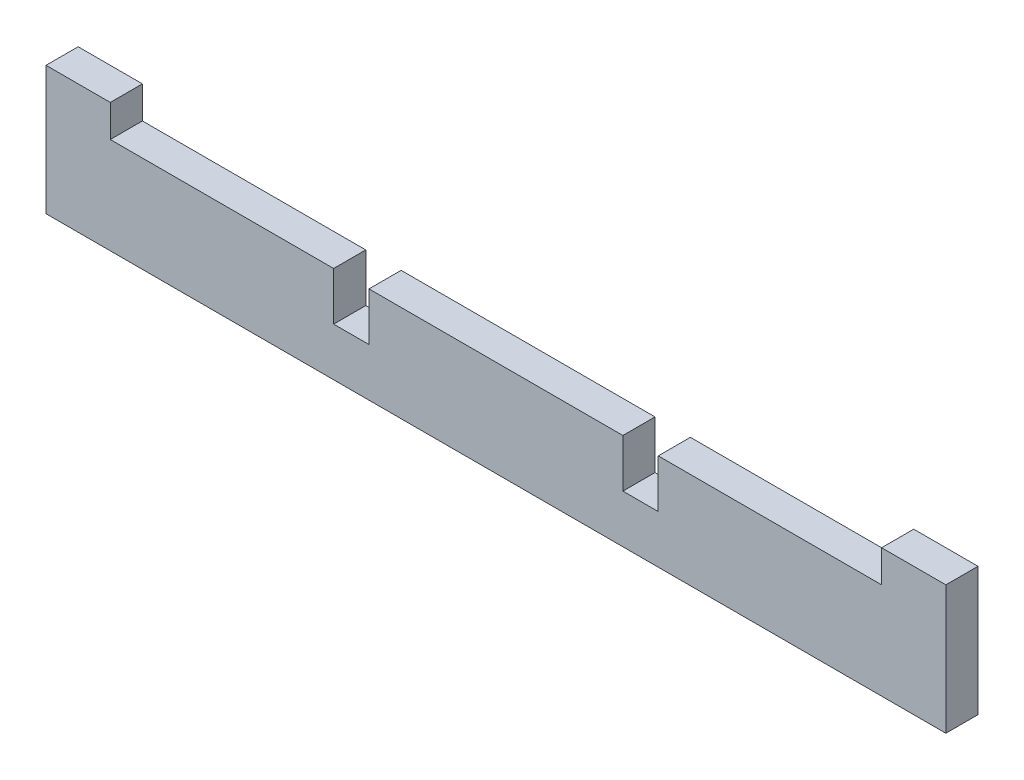
SolidWorks part; units mm, degrees
ref_plane "Front Plane" through (0, 0, 0) normal (0, 0, 1) x (1, 0, 0)
ref_plane "Top Plane" through (0, 0, 0) normal (0, 1, 0) x (1, 0, 0)
ref_plane "Right Plane" through (0, 0, 0) normal (1, 0, 0) x (0, 0, -1)
sketch "Model" plane through (0, 0, 0) normal (0, 0, 1) x (1, 0, 0)
  line L0 (628.5305, -196.1456) -> (628.5305, -188.6456)
  line L1 (663.2805, -183.6456) -> (673.2805, -183.6456)
  line L2 (543.2805, -183.6456) -> (543.2805, -188.6456)
  line L3 (673.2805, -183.6456) -> (673.2805, -203.6456)
  line L4 (578.0305, -188.6456) -> (578.0305, -196.1456)
  line L5 (533.2805, -203.6456) -> (533.2805, -183.6456)
  line L6 (663.2805, -188.6456) -> (663.2805, -183.6456)
  line L7 (533.2805, -183.6456) -> (543.2805, -183.6456)
  line L8 (543.2805, -188.6456) -> (578.0305, -188.6456)
  line L9 (583.5305, -188.6456) -> (623.0305, -188.6456)
  line L10 (663.2805, -188.6456) -> (628.5305, -188.6456)
  line L11 (623.0305, -188.6456) -> (623.0305, -196.1456)
  line L12 (583.5305, -196.1456) -> (583.5305, -188.6456)
  line L13 (578.0305, -196.1456) -> (583.5305, -196.1456)
  line L14 (623.0305, -196.1456) -> (628.5305, -196.1456)
  line L15 (673.2805, -203.6456) -> (533.2805, -203.6456)
  line L16 (607.4013, -190.2081) -> (607.4013, -192.4059)
  line L17 (607.4013, -192.4059) -> (606.3836, -192.4059)
  line L18 (606.3836, -192.4059) -> (605.8263, -192.3372)
  line L19 (605.8263, -192.3372) -> (605.4907, -192.2311)
  line L20 (605.4907, -192.2311) -> (605.3174, -192.0968)
  line L21 (605.3174, -192.0968) -> (605.2597, -191.9439)
  line L22 (605.2597, -191.9439) -> (605.2597, -190.6889)
  line L23 (605.2597, -190.6889) -> (605.2804, -190.5901)
  line L24 (605.2804, -190.5901) -> (605.3424, -190.5)
  line L25 (605.3424, -190.5) -> (605.5906, -190.3454)
  line L26 (605.5906, -190.3454) -> (605.9512, -190.2424)
  line L27 (605.9512, -190.2424) -> (606.3836, -190.2081)
  line L28 (606.3836, -190.2081) -> (607.4013, -190.2081)
  line L29 (607.4013, -194.516) -> (607.4013, -190.2081)
  line L30 (607.4013, -190.2081) -> (606.3836, -190.2081)
  line L31 (606.3836, -190.2081) -> (605.9512, -190.2424)
  line L32 (605.9512, -190.2424) -> (605.5906, -190.3454)
  line L33 (605.5906, -190.3454) -> (605.3424, -190.4999)
  line L34 (605.3424, -190.4999) -> (605.2804, -190.5901)
  line L35 (605.2804, -190.5901) -> (605.2597, -190.6888)
  line L36 (605.2597, -190.6888) -> (605.2597, -191.9437)
  line L37 (605.2597, -191.9437) -> (605.3174, -192.0967)
  line L38 (605.3174, -192.0967) -> (605.4907, -192.2309)
  line L39 (605.4907, -192.2309) -> (605.8263, -192.337)
  line L40 (605.8263, -192.337) -> (606.3836, -192.4057)
  line L41 (606.3836, -192.4057) -> (605.8326, -192.4697)
  line L42 (605.8326, -192.4697) -> (605.4907, -192.5743)
  line L43 (605.4907, -192.5743) -> (605.3174, -192.7132)
  line L44 (605.3174, -192.7132) -> (605.2597, -192.8677)
  line L45 (605.2597, -192.8677) -> (605.2597, -194.0352)
  line L46 (605.2597, -194.0352) -> (605.2804, -194.1289)
  line L47 (605.2804, -194.1289) -> (605.3424, -194.2163)
  line L48 (605.3424, -194.2163) -> (605.5906, -194.3724)
  line L49 (605.5906, -194.3724) -> (605.9543, -194.4801)
  line L50 (605.9543, -194.4801) -> (606.3836, -194.516)
  line L51 (606.3836, -194.516) -> (607.4013, -194.516)
  line L52 (606.3836, -192.4055) -> (607.4013, -192.4055)
  line L53 (607.4013, -192.4055) -> (607.4013, -194.516)
  line L54 (607.4013, -194.516) -> (606.3836, -194.516)
  line L55 (606.3836, -194.516) -> (605.9543, -194.4801)
  line L56 (605.9543, -194.4801) -> (605.5906, -194.3724)
  line L57 (605.5906, -194.3724) -> (605.3424, -194.2163)
  line L58 (605.3424, -194.2163) -> (605.2804, -194.1288)
  line L59 (605.2804, -194.1288) -> (605.2597, -194.0352)
  line L60 (605.2597, -194.0352) -> (605.2597, -192.8676)
  line L61 (605.2597, -192.8676) -> (605.3174, -192.713)
  line L62 (605.3174, -192.713) -> (605.4907, -192.5741)
  line L63 (605.4907, -192.5741) -> (605.8326, -192.4695)
  line L64 (605.8326, -192.4695) -> (606.3836, -192.4055)
  line L65 (604.4044, -190.2081) -> (604.4044, -194.516)
  line L66 (604.4044, -194.516) -> (602.2752, -194.516)
  line L67 (602.2752, -194.516) -> (604.4044, -194.516)
  line L68 (604.4044, -194.516) -> (604.4044, -192.4245)
  line L69 (604.4044, -192.4245) -> (602.5749, -192.4245)
  line L70 (602.5749, -192.4245) -> (604.4044, -192.4245)
  line L71 (604.4044, -192.4245) -> (604.4044, -190.2081)
  line L72 (604.4044, -190.2081) -> (602.2752, -190.2081)
  line L73 (602.2752, -190.2081) -> (604.4044, -190.2081)
  line L74 (600.2835, -190.2081) -> (600.7245, -190.2432)
  line L75 (600.7245, -190.2432) -> (601.0859, -190.3485)
  line L76 (601.0859, -190.3485) -> (601.3271, -190.5038)
  line L77 (601.3271, -190.5038) -> (601.3873, -190.5926)
  line L78 (601.3873, -190.5926) -> (601.4074, -190.6888)
  line L79 (601.4074, -190.6888) -> (601.3873, -190.5926)
  line L80 (601.3873, -190.5926) -> (601.3271, -190.5038)
  line L81 (601.3271, -190.5038) -> (601.0859, -190.3485)
  line L82 (601.0859, -190.3485) -> (600.7245, -190.2432)
  line L83 (599.8425, -190.2432) -> (599.4812, -190.3485)
  line L84 (599.4812, -190.3485) -> (599.24, -190.5038)
  line L85 (599.24, -190.5038) -> (599.1797, -190.5926)
  line L86 (599.1797, -190.5926) -> (599.1596, -190.6888)
  line L87 (599.1596, -190.6888) -> (599.1596, -192.3995)
  line L88 (599.1596, -192.3995) -> (599.1797, -192.4957)
  line L89 (599.1797, -192.4957) -> (599.24, -192.5845)
  line L90 (599.24, -192.5845) -> (599.4812, -192.7398)
  line L91 (599.4812, -192.7398) -> (599.8425, -192.8451)
  line L92 (599.8425, -192.8451) -> (600.2835, -192.8803)
  line L93 (600.2835, -192.8803) -> (600.9579, -192.7803)
  line L94 (600.9579, -192.7803) -> (601.1889, -192.6539)
  line L95 (601.1889, -192.6539) -> (601.4074, -192.3995)
  line L96 (601.4074, -192.3995) -> (601.4074, -194.516)
  line L97 (601.4074, -194.516) -> (599.2346, -194.516)
  line L98 (599.2346, -194.516) -> (601.4074, -194.516)
  line L99 (601.4074, -194.516) -> (601.4074, -192.3995)
  line L100 (601.4074, -192.3995) -> (601.1889, -192.6539)
  line L101 (601.1889, -192.6539) -> (600.9579, -192.7803)
  line L102 (600.9579, -192.7803) -> (600.2835, -192.8803)
  line L103 (600.2835, -192.8803) -> (599.8425, -192.8451)
  line L104 (599.8425, -192.8451) -> (599.4812, -192.7398)
  line L105 (599.4812, -192.7398) -> (599.24, -192.5845)
  line L106 (599.24, -192.5845) -> (599.1797, -192.4957)
  line L107 (599.1797, -192.4957) -> (599.1596, -192.3995)
  line L108 (599.1596, -192.3995) -> (599.1596, -190.6888)
  line L109 (599.1596, -190.6888) -> (599.1797, -190.5926)
  line L110 (599.1797, -190.5926) -> (599.24, -190.5038)
  line L111 (599.24, -190.5038) -> (599.4812, -190.3485)
  line L112 (599.4812, -190.3485) -> (599.8425, -190.2432)
  line L113 (599.8425, -190.2432) -> (600.2835, -190.2081)
  line L114 (609.9013, -192.3956) -> (614.9013, -192.3956)
  line L115 (612.9013, -193.3956) -> (614.9013, -192.3956)
  line L116 (612.9013, -191.3956) -> (614.9013, -192.3956)
  line L117 (596.6596, -192.3956) -> (591.6596, -192.3956)
  line L118 (593.6596, -191.3956) -> (591.6596, -192.3956)
  line L119 (593.6596, -193.3956) -> (591.6596, -192.3956)
  line L120 (538.2805, -190.6456) -> (538.2805, -185.6456)
  line L121 (539.2805, -187.6456) -> (538.2805, -185.6456)
  line L122 (537.2805, -187.6456) -> (538.2805, -185.6456)
  line L123 (542.4013, -191.6456) -> (542.4013, -193.8434)
  line L124 (542.4013, -193.8434) -> (541.3836, -193.8434)
  line L125 (541.3836, -193.8434) -> (540.8263, -193.7747)
  line L126 (540.8263, -193.7747) -> (540.4907, -193.6686)
  line L127 (540.4907, -193.6686) -> (540.3174, -193.5343)
  line L128 (540.3174, -193.5343) -> (540.2597, -193.3814)
  line L129 (540.2597, -193.3814) -> (540.2597, -192.1264)
  line L130 (540.2597, -192.1264) -> (540.2804, -192.0276)
  line L131 (540.2804, -192.0276) -> (540.3424, -191.9375)
  line L132 (540.3424, -191.9375) -> (540.5906, -191.7829)
  line L133 (540.5906, -191.7829) -> (540.9512, -191.6799)
  line L134 (540.9512, -191.6799) -> (541.3836, -191.6456)
  line L135 (541.3836, -191.6456) -> (542.4013, -191.6456)
  line L136 (542.4013, -195.9535) -> (542.4013, -191.6456)
  line L137 (542.4013, -191.6456) -> (541.3836, -191.6456)
  line L138 (541.3836, -191.6456) -> (540.9512, -191.6799)
  line L139 (540.9512, -191.6799) -> (540.5906, -191.7829)
  line L140 (540.5906, -191.7829) -> (540.3424, -191.9374)
  line L141 (540.3424, -191.9374) -> (540.2804, -192.0276)
  line L142 (540.2804, -192.0276) -> (540.2597, -192.1263)
  line L143 (540.2597, -192.1263) -> (540.2597, -193.3812)
  line L144 (540.2597, -193.3812) -> (540.3174, -193.5342)
  line L145 (540.3174, -193.5342) -> (540.4907, -193.6684)
  line L146 (540.4907, -193.6684) -> (540.8263, -193.7745)
  line L147 (540.8263, -193.7745) -> (541.3836, -193.8432)
  line L148 (541.3836, -193.8432) -> (540.8326, -193.9072)
  line L149 (540.8326, -193.9072) -> (540.4907, -194.0118)
  line L150 (540.4907, -194.0118) -> (540.3174, -194.1507)
  line L151 (540.3174, -194.1507) -> (540.2597, -194.3052)
  line L152 (540.2597, -194.3052) -> (540.2597, -195.4727)
  line L153 (540.2597, -195.4727) -> (540.2804, -195.5664)
  line L154 (540.2804, -195.5664) -> (540.3424, -195.6538)
  line L155 (540.3424, -195.6538) -> (540.5906, -195.8099)
  line L156 (540.5906, -195.8099) -> (540.9543, -195.9176)
  line L157 (540.9543, -195.9176) -> (541.3836, -195.9535)
  line L158 (541.3836, -195.9535) -> (542.4013, -195.9535)
  line L159 (541.3836, -193.843) -> (542.4013, -193.843)
  line L160 (542.4013, -193.843) -> (542.4013, -195.9535)
  line L161 (542.4013, -195.9535) -> (541.3836, -195.9535)
  line L162 (541.3836, -195.9535) -> (540.9543, -195.9176)
  line L163 (540.9543, -195.9176) -> (540.5906, -195.8099)
  line L164 (540.5906, -195.8099) -> (540.3424, -195.6538)
  line L165 (540.3424, -195.6538) -> (540.2804, -195.5663)
  line L166 (540.2804, -195.5663) -> (540.2597, -195.4727)
  line L167 (540.2597, -195.4727) -> (540.2597, -194.3051)
  line L168 (540.2597, -194.3051) -> (540.3174, -194.1505)
  line L169 (540.3174, -194.1505) -> (540.4907, -194.0116)
  line L170 (540.4907, -194.0116) -> (540.8326, -193.907)
  line L171 (540.8326, -193.907) -> (541.3836, -193.843)
  line L172 (539.4044, -191.6456) -> (539.4044, -195.9535)
  line L173 (539.4044, -195.9535) -> (538.3866, -195.9535)
  line L174 (538.3866, -195.9535) -> (537.9527, -195.9176)
  line L175 (537.9527, -195.9176) -> (537.5874, -195.8099)
  line L176 (537.5874, -195.8099) -> (537.3439, -195.6538)
  line L177 (537.3439, -195.6538) -> (537.283, -195.5664)
  line L178 (537.283, -195.5664) -> (537.2627, -195.4727)
  line L179 (537.2627, -195.4727) -> (537.2627, -192.1263)
  line L180 (537.2627, -192.1263) -> (537.283, -192.0299)
  line L181 (537.283, -192.0299) -> (537.3439, -191.9406)
  line L182 (537.3439, -191.9406) -> (537.5874, -191.7829)
  line L183 (537.5874, -191.7829) -> (537.9433, -191.6799)
  line L184 (537.9433, -191.6799) -> (538.3866, -191.6456)
  line L185 (538.3866, -191.6456) -> (539.4044, -191.6456)
  line L186 (539.4044, -195.9535) -> (539.4044, -191.6456)
  line L187 (539.4044, -191.6456) -> (538.3866, -191.6456)
  line L188 (538.3866, -191.6456) -> (537.9433, -191.6799)
  line L189 (537.9433, -191.6799) -> (537.5874, -191.7829)
  line L190 (537.5874, -191.7829) -> (537.3439, -191.9406)
  line L191 (537.3439, -191.9406) -> (537.283, -192.0299)
  line L192 (537.283, -192.0299) -> (537.2627, -192.1263)
  line L193 (537.2627, -192.1263) -> (537.2627, -195.4727)
  line L194 (537.2627, -195.4727) -> (537.283, -195.5664)
  line L195 (537.283, -195.5664) -> (537.3439, -195.6538)
  line L196 (537.3439, -195.6538) -> (537.5874, -195.8099)
  line L197 (537.5874, -195.8099) -> (537.9527, -195.9176)
  line L198 (537.9527, -195.9176) -> (538.3866, -195.9535)
  line L199 (538.3866, -195.9535) -> (539.4044, -195.9535)
  line L200 (535.2835, -191.6456) -> (535.7245, -191.6807)
  line L201 (535.7245, -191.6807) -> (536.0859, -191.786)
  line L202 (536.0859, -191.786) -> (536.3271, -191.9413)
  line L203 (536.3271, -191.9413) -> (536.3873, -192.0301)
  line L204 (536.3873, -192.0301) -> (536.4074, -192.1263)
  line L205 (536.4074, -192.1263) -> (536.3873, -192.0301)
  line L206 (536.3873, -192.0301) -> (536.3271, -191.9413)
  line L207 (536.3271, -191.9413) -> (536.0859, -191.786)
  line L208 (536.0859, -191.786) -> (535.7245, -191.6807)
  line L209 (534.8425, -191.6807) -> (534.4812, -191.786)
  line L210 (534.4812, -191.786) -> (534.24, -191.9413)
  line L211 (534.24, -191.9413) -> (534.1797, -192.0301)
  line L212 (534.1797, -192.0301) -> (534.1596, -192.1263)
  line L213 (534.1596, -192.1263) -> (534.1596, -193.837)
  line L214 (534.1596, -193.837) -> (534.1797, -193.9332)
  line L215 (534.1797, -193.9332) -> (534.24, -194.022)
  line L216 (534.24, -194.022) -> (534.4812, -194.1773)
  line L217 (534.4812, -194.1773) -> (534.8425, -194.2826)
  line L218 (534.8425, -194.2826) -> (535.2835, -194.3178)
  line L219 (535.2835, -194.3178) -> (535.9579, -194.2178)
  line L220 (535.9579, -194.2178) -> (536.1889, -194.0914)
  line L221 (536.1889, -194.0914) -> (536.4074, -193.837)
  line L222 (536.4074, -193.837) -> (536.4074, -195.9535)
  line L223 (536.4074, -195.9535) -> (534.2346, -195.9535)
  line L224 (534.2346, -195.9535) -> (536.4074, -195.9535)
  line L225 (536.4074, -195.9535) -> (536.4074, -193.837)
  line L226 (536.4074, -193.837) -> (536.1889, -194.0914)
  line L227 (536.1889, -194.0914) -> (535.9579, -194.2178)
  line L228 (535.9579, -194.2178) -> (535.2835, -194.3178)
  line L229 (535.2835, -194.3178) -> (534.8425, -194.2826)
  line L230 (534.8425, -194.2826) -> (534.4812, -194.1773)
  line L231 (534.4812, -194.1773) -> (534.24, -194.022)
  line L232 (534.24, -194.022) -> (534.1797, -193.9332)
  line L233 (534.1797, -193.9332) -> (534.1596, -193.837)
  line L234 (534.1596, -193.837) -> (534.1596, -192.1263)
  line L235 (534.1596, -192.1263) -> (534.1797, -192.0301)
  line L236 (534.1797, -192.0301) -> (534.24, -191.9413)
  line L237 (534.24, -191.9413) -> (534.4812, -191.786)
  line L238 (534.4812, -191.786) -> (534.8425, -191.6807)
  line L239 (534.8425, -191.6807) -> (535.2835, -191.6456)
  line L240 (640.7186, -192.7158) -> (641.4414, -192.9265)
  line L241 (650.9222, -196.9039) -> (652.0367, -197.0412)
  line L242 (648.0784, -192.6456) -> (648.0784, -197.0034)
  line L243 (649.9044, -197.6558) -> (650.251, -197.3776)
  line L244 (650.251, -196.6916) -> (650.9222, -196.9039)
  line L245 (649.8303, -193.4097) -> (649.7889, -193.6072)
  line L246 (649.8303, -193.4097) -> (649.9544, -193.2293)
  line L247 (650.9347, -197.1685) -> (650.251, -197.3776)
  line L248 (652.0367, -201.2614) -> (654.0723, -201.2614)
  line L249 (652.0367, -197.0412) -> (654.0723, -197.0412)
  line L250 (650.4508, -200.9743) -> (649.9544, -200.662)
  line L251 (649.9544, -200.662) -> (649.8303, -200.4872)
  line L252 (649.7889, -197.9646) -> (649.7889, -200.2998)
  line L253 (654.0723, -201.2614) -> (654.0723, -197.0412)
  line L254 (649.9544, -193.2293) -> (650.4508, -192.9203)
  line L255 (648.0784, -197.0034) -> (644.4194, -197.0034)
  line L256 (652.0367, -192.6456) -> (651.172, -192.7143)
  line L257 (651.1782, -201.1896) -> (650.4508, -200.9743)
  line L258 (651.172, -192.7143) -> (650.4508, -192.9203)
  line L259 (654.0723, -192.6456) -> (652.0367, -192.6456)
  line L260 (652.0367, -197.0412) -> (650.9347, -197.1685)
  line L261 (652.0367, -201.2614) -> (651.1782, -201.1896)
  line L262 (648.0784, -201.2614) -> (643.82, -201.2614)
  line L263 (654.0723, -197.0412) -> (654.0723, -192.6456)
  line L264 (649.7889, -200.2998) -> (649.8303, -200.4872)
  line L265 (639.8366, -192.6456) -> (640.7186, -192.7158)
  line L266 (641.9237, -193.2371) -> (642.0443, -193.4147)
  line L267 (642.0443, -193.4147) -> (642.0845, -193.6071)
  line L268 (650.251, -196.6916) -> (649.9044, -196.4231)
  line L269 (649.7889, -193.6072) -> (649.7889, -196.1172)
  line L270 (641.9237, -193.2371) -> (641.4414, -192.9265)
  line L271 (649.9044, -197.6558) -> (649.7889, -197.9646)
  line L272 (649.7889, -196.1172) -> (649.9044, -196.4231)
  line L273 (637.5888, -193.6071) -> (637.629, -193.4147)
  line L274 (642.0845, -197.0284) -> (641.6474, -197.5373)
  line L275 (638.9547, -197.9197) -> (639.8366, -197.99)
  line L276 (641.1854, -197.7901) -> (639.8366, -197.99)
  line L277 (638.9547, -197.9197) -> (638.2319, -197.709)
  line L278 (641.6474, -197.5373) -> (641.1854, -197.7901)
  line L279 (637.7496, -193.2371) -> (638.2319, -192.9265)
  line L280 (642.0845, -201.2614) -> (637.7387, -201.2614)
  line L281 (637.629, -193.4147) -> (637.7496, -193.2371)
  line L282 (648.0784, -197.0034) -> (648.0784, -201.2614)
  line L283 (637.7496, -197.3984) -> (637.629, -197.2208)
  line L284 (638.2319, -192.9265) -> (638.9547, -192.7158)
  line L285 (637.5888, -193.6071) -> (637.5888, -197.0284)
  line L286 (637.5888, -197.0284) -> (637.629, -197.2208)
  line L287 (637.7496, -197.3984) -> (638.2319, -197.709)
  line L288 (642.0845, -201.2614) -> (642.0845, -197.0284)
  line L289 (638.9547, -192.7158) -> (639.8366, -192.6456)
  line L290 (654.0723, -191.6456) -> (637.7387, -191.6456)
  line L291 (668.2805, -190.6456) -> (668.2805, -185.6456)
  line L292 (669.2805, -187.6456) -> (668.2805, -185.6456)
  line L293 (667.2805, -187.6456) -> (668.2805, -185.6456)
  line L294 (672.4013, -191.6456) -> (672.4013, -193.8434)
  line L295 (672.4013, -193.8434) -> (671.3836, -193.8434)
  line L296 (671.3836, -193.8434) -> (670.8263, -193.7747)
  line L297 (670.8263, -193.7747) -> (670.4907, -193.6686)
  line L298 (670.4907, -193.6686) -> (670.3174, -193.5343)
  line L299 (670.3174, -193.5343) -> (670.2597, -193.3814)
  line L300 (670.2597, -193.3814) -> (670.2597, -192.1264)
  line L301 (670.2597, -192.1264) -> (670.2804, -192.0276)
  line L302 (670.2804, -192.0276) -> (670.3424, -191.9375)
  line L303 (670.3424, -191.9375) -> (670.5906, -191.7829)
  line L304 (670.5906, -191.7829) -> (670.9512, -191.6799)
  line L305 (670.9512, -191.6799) -> (671.3836, -191.6456)
  line L306 (671.3836, -191.6456) -> (672.4013, -191.6456)
  line L307 (672.4013, -195.9535) -> (672.4013, -191.6456)
  line L308 (672.4013, -191.6456) -> (671.3836, -191.6456)
  line L309 (671.3836, -191.6456) -> (670.9512, -191.6799)
  line L310 (670.9512, -191.6799) -> (670.5906, -191.7829)
  line L311 (670.5906, -191.7829) -> (670.3424, -191.9374)
  line L312 (670.3424, -191.9374) -> (670.2804, -192.0276)
  line L313 (670.2804, -192.0276) -> (670.2597, -192.1263)
  line L314 (670.2597, -192.1263) -> (670.2597, -193.3812)
  line L315 (670.2597, -193.3812) -> (670.3174, -193.5342)
  line L316 (670.3174, -193.5342) -> (670.4907, -193.6684)
  line L317 (670.4907, -193.6684) -> (670.8263, -193.7745)
  line L318 (670.8263, -193.7745) -> (671.3836, -193.8432)
  line L319 (671.3836, -193.8432) -> (670.8326, -193.9072)
  line L320 (670.8326, -193.9072) -> (670.4907, -194.0118)
  line L321 (670.4907, -194.0118) -> (670.3174, -194.1507)
  line L322 (670.3174, -194.1507) -> (670.2597, -194.3052)
  line L323 (670.2597, -194.3052) -> (670.2597, -195.4727)
  line L324 (670.2597, -195.4727) -> (670.2804, -195.5664)
  line L325 (670.2804, -195.5664) -> (670.3424, -195.6538)
  line L326 (670.3424, -195.6538) -> (670.5906, -195.8099)
  line L327 (670.5906, -195.8099) -> (670.9543, -195.9176)
  line L328 (670.9543, -195.9176) -> (671.3836, -195.9535)
  line L329 (671.3836, -195.9535) -> (672.4013, -195.9535)
  line L330 (671.3836, -193.843) -> (672.4013, -193.843)
  line L331 (672.4013, -193.843) -> (672.4013, -195.9535)
  line L332 (672.4013, -195.9535) -> (671.3836, -195.9535)
  line L333 (671.3836, -195.9535) -> (670.9543, -195.9176)
  line L334 (670.9543, -195.9176) -> (670.5906, -195.8099)
  line L335 (670.5906, -195.8099) -> (670.3424, -195.6538)
  line L336 (670.3424, -195.6538) -> (670.2804, -195.5663)
  line L337 (670.2804, -195.5663) -> (670.2597, -195.4727)
  line L338 (670.2597, -195.4727) -> (670.2597, -194.3051)
  line L339 (670.2597, -194.3051) -> (670.3174, -194.1505)
  line L340 (670.3174, -194.1505) -> (670.4907, -194.0116)
  line L341 (670.4907, -194.0116) -> (670.8326, -193.907)
  line L342 (670.8326, -193.907) -> (671.3836, -193.843)
  line L343 (669.4044, -191.6456) -> (669.4044, -195.9535)
  line L344 (669.4044, -195.9535) -> (668.3866, -195.9535)
  line L345 (668.3866, -195.9535) -> (667.9527, -195.9176)
  line L346 (667.9527, -195.9176) -> (667.5874, -195.8099)
  line L347 (667.5874, -195.8099) -> (667.3439, -195.6538)
  line L348 (667.3439, -195.6538) -> (667.283, -195.5664)
  line L349 (667.283, -195.5664) -> (667.2627, -195.4727)
  line L350 (667.2627, -195.4727) -> (667.2627, -192.1263)
  line L351 (667.2627, -192.1263) -> (667.283, -192.0299)
  line L352 (667.283, -192.0299) -> (667.3439, -191.9406)
  line L353 (667.3439, -191.9406) -> (667.5874, -191.7829)
  line L354 (667.5874, -191.7829) -> (667.9433, -191.6799)
  line L355 (667.9433, -191.6799) -> (668.3866, -191.6456)
  line L356 (668.3866, -191.6456) -> (669.4044, -191.6456)
  line L357 (669.4044, -195.9535) -> (669.4044, -191.6456)
  line L358 (669.4044, -191.6456) -> (668.3866, -191.6456)
  line L359 (668.3866, -191.6456) -> (667.9433, -191.6799)
  line L360 (667.9433, -191.6799) -> (667.5874, -191.7829)
  line L361 (667.5874, -191.7829) -> (667.3439, -191.9406)
  line L362 (667.3439, -191.9406) -> (667.283, -192.0299)
  line L363 (667.283, -192.0299) -> (667.2627, -192.1263)
  line L364 (667.2627, -192.1263) -> (667.2627, -195.4727)
  line L365 (667.2627, -195.4727) -> (667.283, -195.5664)
  line L366 (667.283, -195.5664) -> (667.3439, -195.6538)
  line L367 (667.3439, -195.6538) -> (667.5874, -195.8099)
  line L368 (667.5874, -195.8099) -> (667.9527, -195.9176)
  line L369 (667.9527, -195.9176) -> (668.3866, -195.9535)
  line L370 (668.3866, -195.9535) -> (669.4044, -195.9535)
  line L371 (665.2835, -191.6456) -> (665.7245, -191.6807)
  line L372 (665.7245, -191.6807) -> (666.0859, -191.786)
  line L373 (666.0859, -191.786) -> (666.3271, -191.9413)
  line L374 (666.3271, -191.9413) -> (666.3873, -192.0301)
  line L375 (666.3873, -192.0301) -> (666.4074, -192.1263)
  line L376 (666.4074, -192.1263) -> (666.3873, -192.0301)
  line L377 (666.3873, -192.0301) -> (666.3271, -191.9413)
  line L378 (666.3271, -191.9413) -> (666.0859, -191.786)
  line L379 (666.0859, -191.786) -> (665.7245, -191.6807)
  line L380 (664.8425, -191.6807) -> (664.4812, -191.786)
  line L381 (664.4812, -191.786) -> (664.24, -191.9413)
  line L382 (664.24, -191.9413) -> (664.1797, -192.0301)
  line L383 (664.1797, -192.0301) -> (664.1596, -192.1263)
  line L384 (664.1596, -192.1263) -> (664.1596, -193.837)
  line L385 (664.1596, -193.837) -> (664.1797, -193.9332)
  line L386 (664.1797, -193.9332) -> (664.24, -194.022)
  line L387 (664.24, -194.022) -> (664.4812, -194.1773)
  line L388 (664.4812, -194.1773) -> (664.8425, -194.2826)
  line L389 (664.8425, -194.2826) -> (665.2835, -194.3178)
  line L390 (665.2835, -194.3178) -> (665.9579, -194.2178)
  line L391 (665.9579, -194.2178) -> (666.1889, -194.0914)
  line L392 (666.1889, -194.0914) -> (666.4074, -193.837)
  line L393 (666.4074, -193.837) -> (666.4074, -195.9535)
  line L394 (666.4074, -195.9535) -> (664.2346, -195.9535)
  line L395 (664.2346, -195.9535) -> (666.4074, -195.9535)
  line L396 (666.4074, -195.9535) -> (666.4074, -193.837)
  line L397 (666.4074, -193.837) -> (666.1889, -194.0914)
  line L398 (666.1889, -194.0914) -> (665.9579, -194.2178)
  line L399 (665.9579, -194.2178) -> (665.2835, -194.3178)
  line L400 (665.2835, -194.3178) -> (664.8425, -194.2826)
  line L401 (664.8425, -194.2826) -> (664.4812, -194.1773)
  line L402 (664.4812, -194.1773) -> (664.24, -194.022)
  line L403 (664.24, -194.022) -> (664.1797, -193.9332)
  line L404 (664.1797, -193.9332) -> (664.1596, -193.837)
  line L405 (664.1596, -193.837) -> (664.1596, -192.1263)
  line L406 (664.1596, -192.1263) -> (664.1797, -192.0301)
  line L407 (664.1797, -192.0301) -> (664.24, -191.9413)
  line L408 (664.24, -191.9413) -> (664.4812, -191.786)
  line L409 (664.4812, -191.786) -> (664.8425, -191.6807)
  line L410 (664.8425, -191.6807) -> (665.2835, -191.6456)
sketch "Sketch2" plane through (0, 0, 0) normal (0, 0, 1) x (1, 0, 0)
  line L0 (673.2805, -183.6456) -> (673.2805, -203.6456) construction
  line L1 (663.2805, -183.6456) -> (673.2805, -183.6456) construction
  line L2 (663.2805, -188.6456) -> (663.2805, -183.6456) construction
  line L3 (663.2805, -188.6456) -> (628.5305, -188.6456) construction
  line L4 (628.5305, -196.1456) -> (628.5305, -188.6456) construction
  line L5 (623.0305, -196.1456) -> (628.5305, -196.1456) construction
  line L6 (623.0305, -188.6456) -> (623.0305, -196.1456) construction
  line L7 (583.5305, -188.6456) -> (623.0305, -188.6456) construction
  line L8 (583.5305, -196.1456) -> (583.5305, -188.6456) construction
  line L9 (578.0305, -196.1456) -> (583.5305, -196.1456) construction
  line L10 (578.0305, -188.6456) -> (578.0305, -196.1456) construction
  line L11 (543.2805, -188.6456) -> (578.0305, -188.6456) construction
  line L12 (543.2805, -183.6456) -> (543.2805, -188.6456) construction
  line L13 (533.2805, -183.6456) -> (543.2805, -183.6456) construction
  line L14 (533.2805, -203.6456) -> (533.2805, -183.6456) construction
  line L15 (673.2805, -203.6456) -> (533.2805, -203.6456) construction
  line L16 (673.2805, -183.6456) -> (673.2805, -203.6456)
  line L17 (663.2805, -183.6456) -> (673.2805, -183.6456)
  line L18 (663.2805, -188.6456) -> (663.2805, -183.6456)
  line L19 (663.2805, -188.6456) -> (628.5305, -188.6456)
  line L20 (628.5305, -196.1456) -> (628.5305, -188.6456)
  line L21 (623.0305, -196.1456) -> (628.5305, -196.1456)
  line L22 (623.0305, -188.6456) -> (623.0305, -196.1456)
  line L23 (583.5305, -188.6456) -> (623.0305, -188.6456)
  line L24 (583.5305, -196.1456) -> (583.5305, -188.6456)
  line L25 (578.0305, -196.1456) -> (583.5305, -196.1456)
  line L26 (578.0305, -188.6456) -> (578.0305, -196.1456)
  line L27 (543.2805, -188.6456) -> (578.0305, -188.6456)
  line L28 (543.2805, -183.6456) -> (543.2805, -188.6456)
  line L29 (533.2805, -183.6456) -> (543.2805, -183.6456)
  line L30 (533.2805, -203.6456) -> (533.2805, -183.6456)
  line L31 (673.2805, -203.6456) -> (533.2805, -203.6456)
extrude "Boss-Extrude1" add sketch "Sketch2" along normal mid plane 5
ref_plane "Plane1" through (603.2805, 0, 0) normal (1, 0, 0) x (0, 0, -1)
